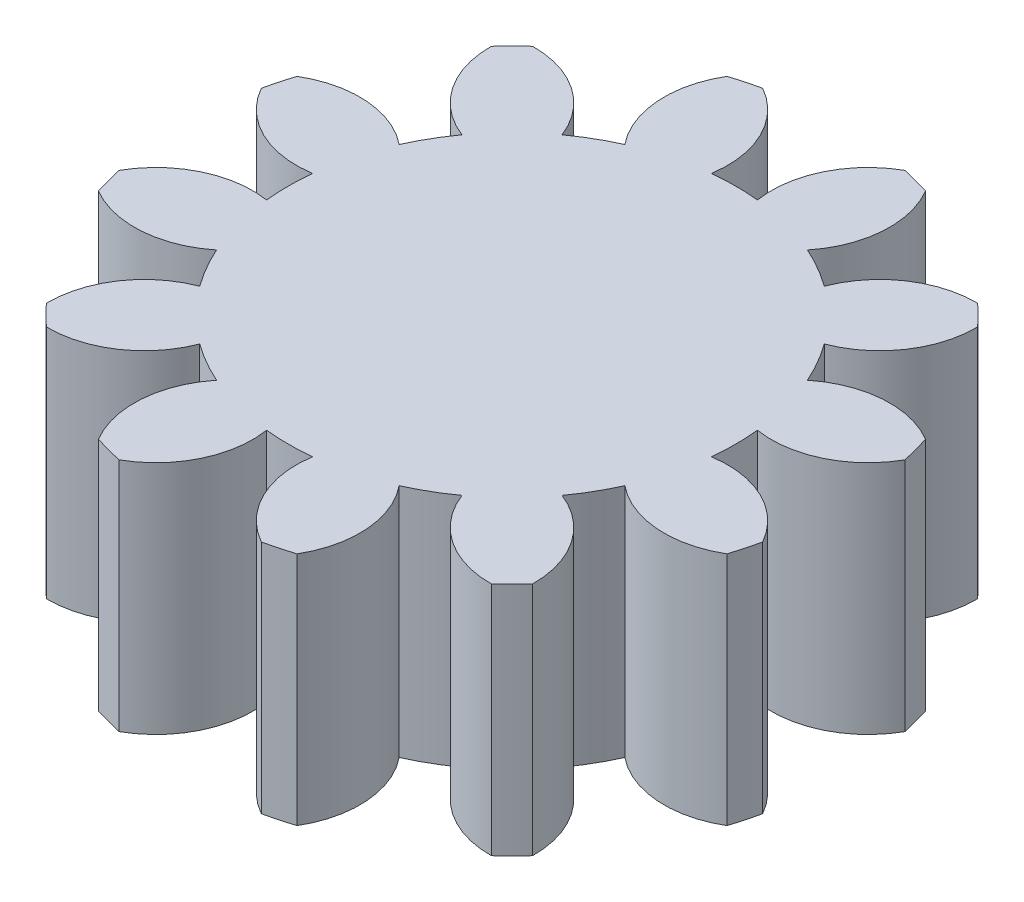
SolidWorks part; units mm, degrees
ref_plane "Front Plane" through (0, 0, 0) normal (0, 0, 1) x (1, 0, 0)
ref_plane "Top Plane" through (0, 0, 0) normal (0, 1, 0) x (1, 0, 0)
ref_plane "Right Plane" through (0, 0, 0) normal (1, 0, 0) x (0, 0, -1)
sketch "Sketch1" plane through (0, 0, 0) normal (0, 1, 0) x (1, 0, 0)
  circle A0 centre (0, 0) radius 4.2
  dimension "D1" = 8.4
extrude "Boss-Extrude1" add sketch "Sketch1" along normal blind 3
sketch "Sketch2" plane through (0, 3, 0) normal (0, 1, 0) x (1, 0, 0)
  line L0 (-0.4075, 3.5769) -> (-1.5102, 3.0266) construction
  line L1 (-1.5102, 3.0266) -> (0, 0) construction
  line L2 (-1.1087, 4.1917) -> (0, 5.9778)
  line L4 (0, 0) -> (-0.4075, 3.5769) construction
  line L5 (0, 0) -> (1.4355, 3.3014) construction
  line L7 (0, 0) -> (0, 2.85) construction
  line L8 (0, 2.85) -> (0, 5.9778)
  circle A0 centre (0, 0) radius 3.3825 construction
  circle A1 centre (0, 0) radius 2.85 construction
  circle A3 centre (0, 0) radius 3.6 construction
  arc A4 (-0.2929, 2.8349) -> (-1.1087, 4.1917) centre (-1.5102, 3.0266) ccw
  arc A5 (-0.2929, 2.8349) -> (0, 2.85) centre (0, 0) cw
  dimension "D2" = 7.2
  dimension "D3" = 6.765
  dimension "D4" = 5.7
  dimension "D8" = 30
  dimension "D9" = 6.5
extrude "Cut-Extrude2" cut sketch "Sketch2" against normal blind 3
ref_plane "Plane2" through (0, 0, 0) normal (-1, 0, 0) x (0, 0, 1)
mirror "Mirror2" about plane through (0, 0, 0) normal (-1, 0, 0) of "Cut-Extrude2"
pattern_circular "CirPattern1" count 12 over 360 about axis through (0, 0, 0) along (0, 1, 0) of "Mirror2", "Cut-Extrude2"
